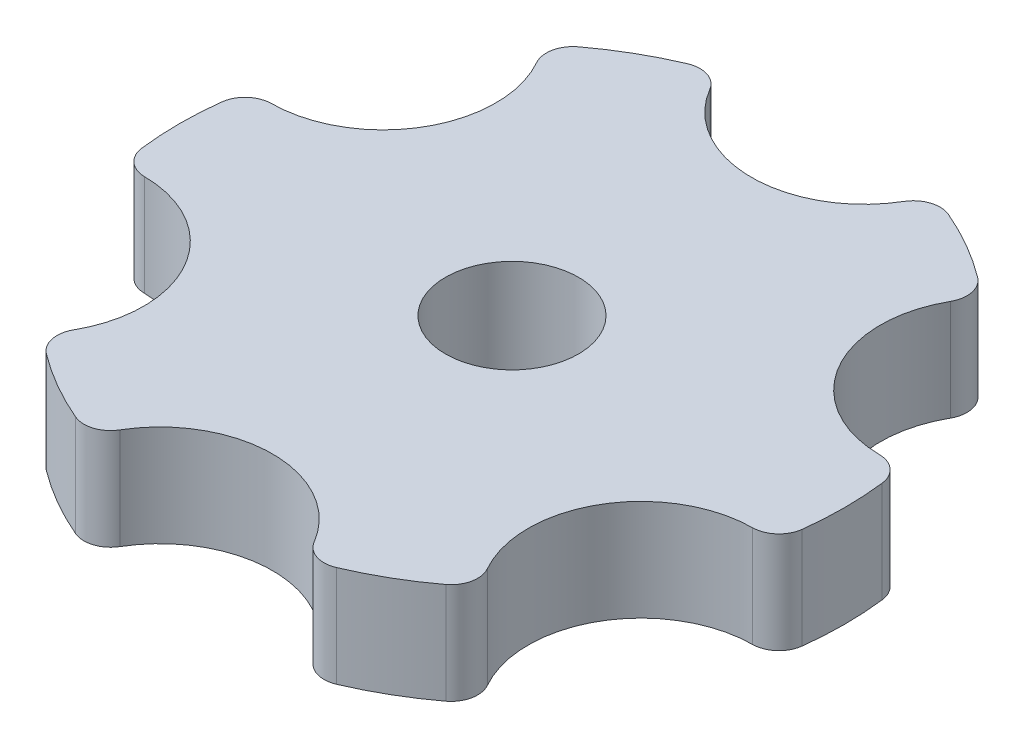
SolidWorks part; units mm, degrees
ref_plane "Front Plane" through (0, 0, 0) normal (0, 0, 1) x (1, 0, 0)
ref_plane "Top Plane" through (0, 0, 0) normal (0, 1, 0) x (1, 0, 0)
ref_plane "Right Plane" through (0, 0, 0) normal (1, 0, 0) x (0, 0, -1)
sketch "Sketch1" plane through (0, 0, 0) normal (0, 1, 0) x (1, 0, 0)
  circle A0 centre (0, 0) radius 31.75 construction
  arc A1 (-10.16, 30.0805) -> (10.16, 30.0805) centre (0, 33.6183) ccw
  arc A2 (20.9705, 23.8391) -> (31.1305, 6.2414) centre (29.1143, 16.8092) ccw
  arc A3 (31.1305, -6.2414) -> (20.9705, -23.8391) centre (29.1143, -16.8092) ccw
  arc A4 (10.16, -30.0805) -> (-10.16, -30.0805) centre (0, -33.6183) ccw
  arc A5 (-20.9705, -23.8391) -> (-31.1305, -6.2414) centre (-29.1143, -16.8092) ccw
  arc A6 (-31.1305, 6.2414) -> (-20.9705, 23.8391) centre (-29.1143, 16.8092) ccw
  arc A7 (-20.9705, 23.8391) -> (-10.16, 30.0805) centre (0, 0) cw
  arc A8 (10.16, 30.0805) -> (20.9705, 23.8391) centre (0, 0) cw
  arc A9 (31.1305, 6.2414) -> (31.1305, -6.2414) centre (0, 0) cw
  arc A10 (20.9705, -23.8391) -> (10.16, -30.0805) centre (0, 0) cw
  arc A11 (-10.16, -30.0805) -> (-20.9705, -23.8391) centre (0, 0) cw
  arc A12 (-31.1305, -6.2414) -> (-31.1305, 6.2414) centre (0, 0) cw
  circle A13 centre (0, 0) radius 6.35
  point P24 (0, 0)
  dimension "D1" = 63.5
  dimension "D3" = 8.89
  dimension "D5" = 12.7
  dimension "D2" = 20.32
  dimension "D4" = 6
extrude "Boss-Extrude1" add sketch "Sketch1" along normal blind 9.652
fillet "Fillet1" radius 2.54 12 edges at (20.9705, 4.826, 23.8391) (31.1305, 4.826, 6.2414) (31.1305, 4.826, -6.2414) (20.9705, 4.826, -23.8391) (10.16, 4.826, -30.0805) (-10.16, 4.826, -30.0805) (-20.9705, 4.826, -23.8391) (-31.1305, 4.826, -6.2414) (-31.1305, 4.826, 6.2414) (-20.9705, 4.826, 23.8391) (10.16, 4.826, 30.0805) (-10.16, 4.826, 30.0805)
